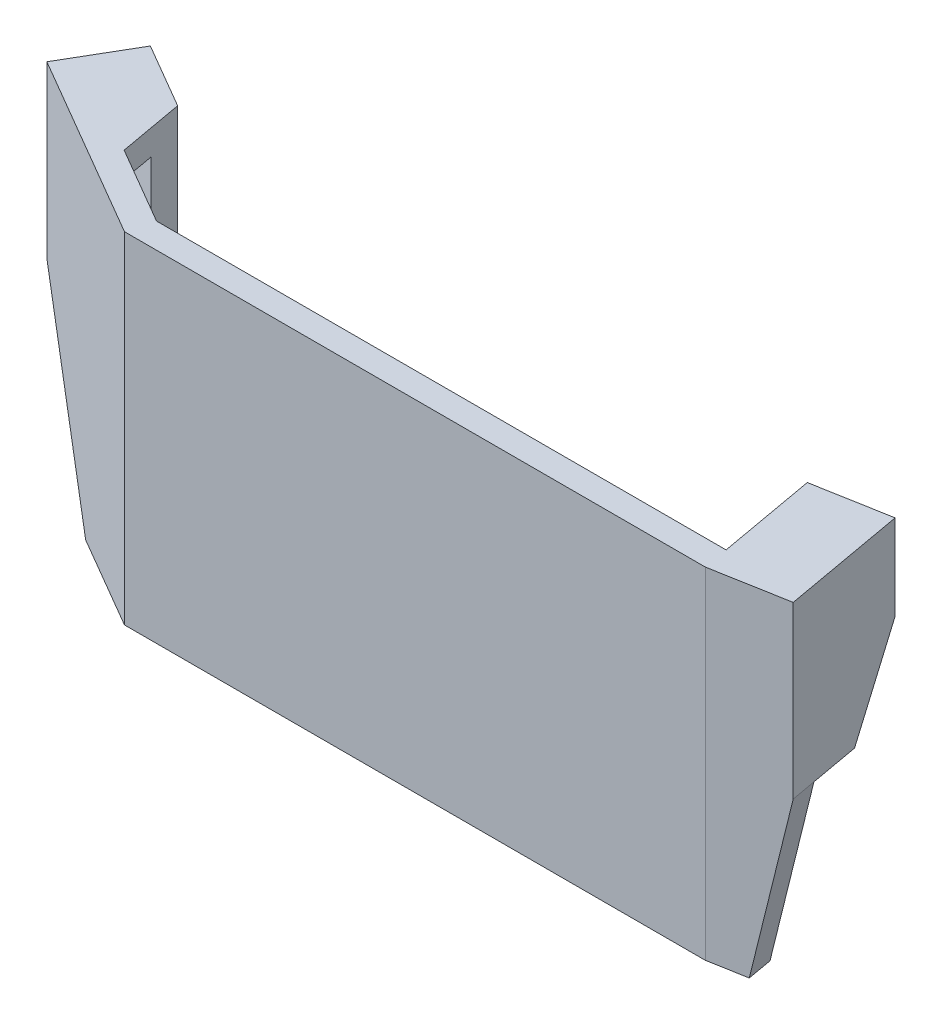
SolidWorks part; units mm, degrees
ref_plane "Front Plane" through (0, 0, 0) normal (0, 0, 1) x (1, 0, 0)
ref_plane "Top Plane" through (0, 0, 0) normal (0, 1, 0) x (1, 0, 0)
ref_plane "Right Plane" through (0, 0, 0) normal (1, 0, 0) x (0, 0, -1)
sketch "Sketch2" plane through (0, 0, 0) normal (0, 1, 0) x (1, 0, 0)
  line L12 (-22.4852, 2) -> (22.6668, 2)
  line L13 (22.6668, 2) -> (21.2607, 9.8431)
  line L14 (23.0254, 0) -> (-23.0254, 0)
  line L15 (28.9312, 1.0588) -> (27.1665, 10.9019)
  line L16 (-28.6378, 5.5849) -> (-22.4852, 2)
  line L17 (27.1665, 10.9019) -> (21.2607, 9.8431)
  line L18 (23.0254, 0) -> (28.9312, 1.0588)
  line L19 (-37.7694, 8.591) -> (-23.0254, 0)
  line L20 (-34.7488, 13.7751) -> (-37.7694, 8.591)
  line L21 (-29.5646, 10.7544) -> (-34.7488, 13.7751)
  line L22 (-29.5646, 10.7544) -> (-28.6378, 5.5849)
  point P0 (0, 0)
  point P2 (0, 0)
  point P3 (0, 0)
  dimension "D1" = 6
  dimension "D2" = 6
  dimension "D3" = 10
  dimension "D4" = 2
  dimension "D5" = 2
  dimension "D6" = 149.772
  dimension "D7" = 79.836
  dimension "D8" = 190.164
  dimension "D9" = 17.0643
  dimension "D10" = 22.664
  dimension "D11" = 46.0508
  dimension "D12" = 5.1695
  dimension "D13" = 7.1208
  dimension "D14" = 7.9681
  dimension "D15" = 6
  dimension "D16" = 27.2027
extrude "Boss-Extrude1" add sketch "Sketch2" against normal blind 2
sketch "Sketch3" plane through (0, -2, 0) normal (0, -1, 0) x (1, 0, 0)
  line L0 (-37.7694, -8.591) -> (-23.0254, 0)
  line L1 (-23.0254, 0) -> (23.0254, 0)
  line L2 (23.0254, 0) -> (28.9312, -1.0588)
  line L8 (-22.4852, -2) -> (-28.6378, -5.5849)
  line L9 (-28.6378, -5.5849) -> (-36.7625, -10.319)
  line L10 (-34.7488, -13.7751) -> (-37.7694, -8.591) construction
  line L11 (-36.7625, -10.319) -> (-37.7694, -8.591)
  line L12 (-22.4852, -2) -> (22.6668, -2)
  line L13 (22.6668, -2) -> (21.2607, -9.8431)
  line L14 (21.2607, -9.8431) -> (23.2293, -10.196)
  line L15 (27.1665, -10.9019) -> (21.2607, -9.8431) construction
  line L16 (23.2293, -10.196) -> (24.6354, -2.3529)
  line L17 (28.9312, -1.0588) -> (28.5727, -3.0588)
  line L18 (28.9312, -1.0588) -> (27.1665, -10.9019) construction
  line L19 (28.5727, -3.0588) -> (24.6354, -2.3529)
  dimension "D1" = 2.0319
  dimension "D2" = 2
extrude "Boss-Extrude2" add sketch "Sketch3" along normal blind 25
sketch "Sketch4" plane through (0, -2, 0) normal (0, -1, 0) x (1, 0, 0)
  line L1 (25.1979, -10.5489) -> (26.6041, -2.7059)
  line L3 (24.6354, -2.3529) -> (28.5727, -3.0588) construction
  line L7 (26.6041, -2.7059) -> (28.5727, -3.0588)
  line L9 (28.5727, -3.0588) -> (27.1665, -10.9019)
  line L10 (-34.7488, -13.7751) -> (-35.7556, -12.0471)
  line L11 (-34.7488, -13.7751) -> (-36.7625, -10.319) construction
  line L12 (-35.7556, -12.0471) -> (-29.1012, -8.1697)
  line L13 (-28.6378, -5.5849) -> (-29.5646, -10.7544) construction
  line L14 (-29.1012, -8.1697) -> (-29.5646, -10.7544)
  line L15 (-29.5646, -10.7544) -> (-34.7488, -13.7751)
  line L18 (27.1665, -10.9019) -> (25.1979, -10.5489)
  line L19 (27.1665, -10.9019) -> (23.2293, -10.196) construction
  dimension "D1" = 2
  dimension "D2" = 2
extrude "Boss-Extrude3" add sketch "Sketch4" along normal blind 11.5
sketch "Sketch5" plane through (-5.836, 0, 10.0158) normal (-0.5034, 0, 0.864) x (0.864, 0, 0.5034)
  line L0 (-28.4267, -27) -> (-36.9589, -13.5)
  line L1 (-19.8946, -27) -> (-36.9589, -27) construction
  line L2 (-36.9589, -27) -> (-36.9589, 0) construction
  line L3 (-36.9589, -13.5) -> (-36.9589, -27)
  line L4 (-36.9589, -27) -> (-28.4267, -27)
extrude "Cut-Extrude2" cut sketch "Sketch5" against normal up to surface (2 mm away) up to face at (-29.2952, -9.6667, -5.968)
sketch "Sketch6" plane through (0.7171, 0, 3.9996) normal (0.1765, 0, 0.9843) x (0.9843, 0, -0.1765)
  line L5 (28.664, -27) -> (22.664, -27) construction
  line L6 (25.664, -27) -> (28.664, -27)
  line L8 (28.664, -13.5) -> (25.664, -27)
  line L9 (28.664, -27) -> (28.664, 0) construction
  line L10 (28.664, -27) -> (28.664, -13.5)
extrude "Cut-Extrude3" cut sketch "Sketch6" against normal up to surface (2.0319 mm away) up to face at (26.6041, -14.1667, -2.7059)
sketch "Sketch8" plane through (24.2769, 0, -4.3525) normal (0.9843, 0, -0.1765) x (-0.1765, 0, -0.9843)
  line L0 (-2.0315, -13.5) -> (5.9366, -13.5)
  line L1 (5.9366, -13.5) -> (5.9366, -27)
  line L2 (5.9366, -27) -> (-2.0315, -27)
  line L3 (-2.0315, -27) -> (-2.0315, -13.5)
extrude "Cut-Extrude4" cut sketch "Sketch8" against normal up to surface (2 mm away) up to face at (21.9638, -13.5, -5.9215)
sketch "Sketch9" plane through (28.2142, 0, -5.0584) normal (0.9843, 0, -0.1765) x (-0.1765, 0, -0.9843)
  line L0 (1.9526, -13.5) -> (5.9366, -6.75)
  line L1 (5.9366, -13.5) -> (-2.0315, -13.5) construction
  line L2 (5.9366, -13.5) -> (5.9366, 0) construction
  line L3 (5.9366, -6.75) -> (5.9366, -13.5)
  line L4 (5.9366, -27) -> (5.9366, 0) construction
  line L5 (5.9366, -13.5) -> (1.9526, -13.5)
extrude "Cut-Extrude5" cut sketch "Sketch9" against normal up to surface (6 mm away) up to face at (21.9638, -6.75, -5.9215)
sketch "Sketch10" plane through (-2.8153, 0, 4.8317) normal (0.5034, 0, -0.864) x (-0.864, 0, -0.5034)
  line L0 (36.9589, -6.75) -> (33.9589, -13.5)
  line L1 (36.9589, -13.5) -> (36.9589, 0) construction
  line L2 (36.9589, -13.5) -> (30.9589, -13.5) construction
  line L3 (33.9589, -13.5) -> (36.9589, -13.5)
  line L4 (36.9589, -13.5) -> (36.9589, -6.75)
extrude "Cut-Extrude6" cut sketch "Sketch10" against normal up to surface (2 mm away) up to face at (-32.4284, -7.75, -10.1084)
